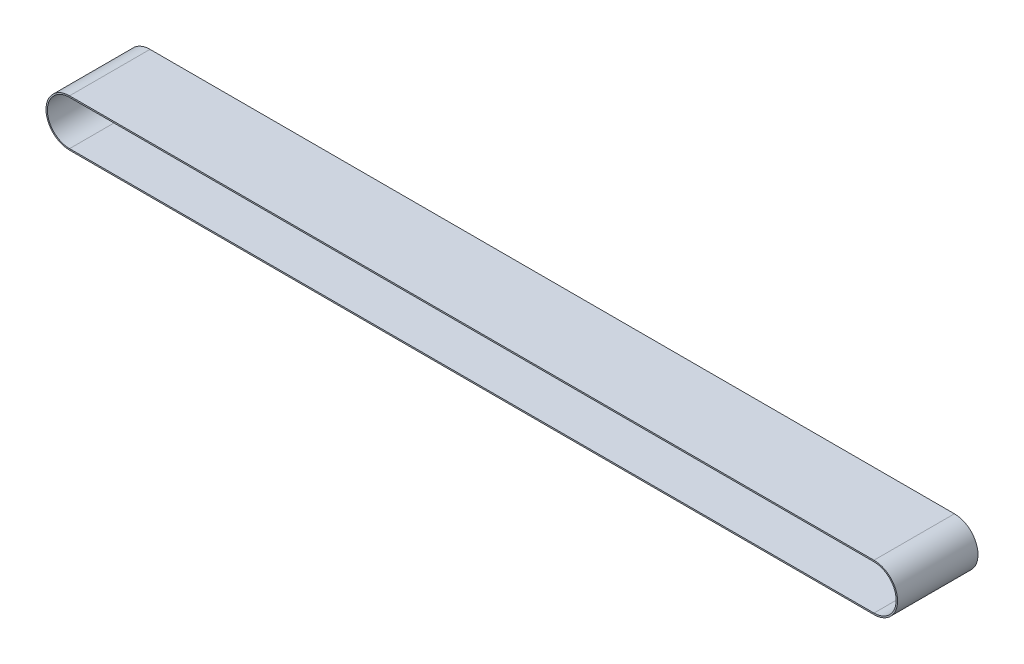
SolidWorks part; units mm, degrees
ref_plane "Front Plane" through (0, 0, 0) normal (0, 0, 1) x (1, 0, 0)
ref_plane "Top Plane" through (0, 0, 0) normal (0, 1, 0) x (1, 0, 0)
ref_plane "Right Plane" through (0, 0, 0) normal (1, 0, 0) x (0, 0, -1)
sketch "Sketch1" plane through (0, 0, 0) normal (0, 0, 1) x (1, 0, 0)
  line L0 (0, 0) -> (580, 0) construction
  line L1 (0, 16) -> (580, 16)
  line L2 (0, -16) -> (580, -16)
  line L3 (0, 0) -> (580, 0) construction
  line L4 (0, 17) -> (580, 17)
  line L5 (0, -17) -> (580, -17)
  arc A0 (0, 16) -> (0, -16) centre (0, 0) ccw
  arc A1 (580, -16) -> (580, 16) centre (580, 0) ccw
  arc A2 (0, 17) -> (0, -17) centre (0, 0) ccw
  arc A3 (580, -17) -> (580, 17) centre (580, 0) ccw
  point P3 (290, 0)
  point P10 (290, 0)
  dimension "D2" = 32
  dimension "D3" = 34
  dimension "D1" = 580
extrude "Boss-Extrude1" add sketch "Sketch1" along normal blind 58
